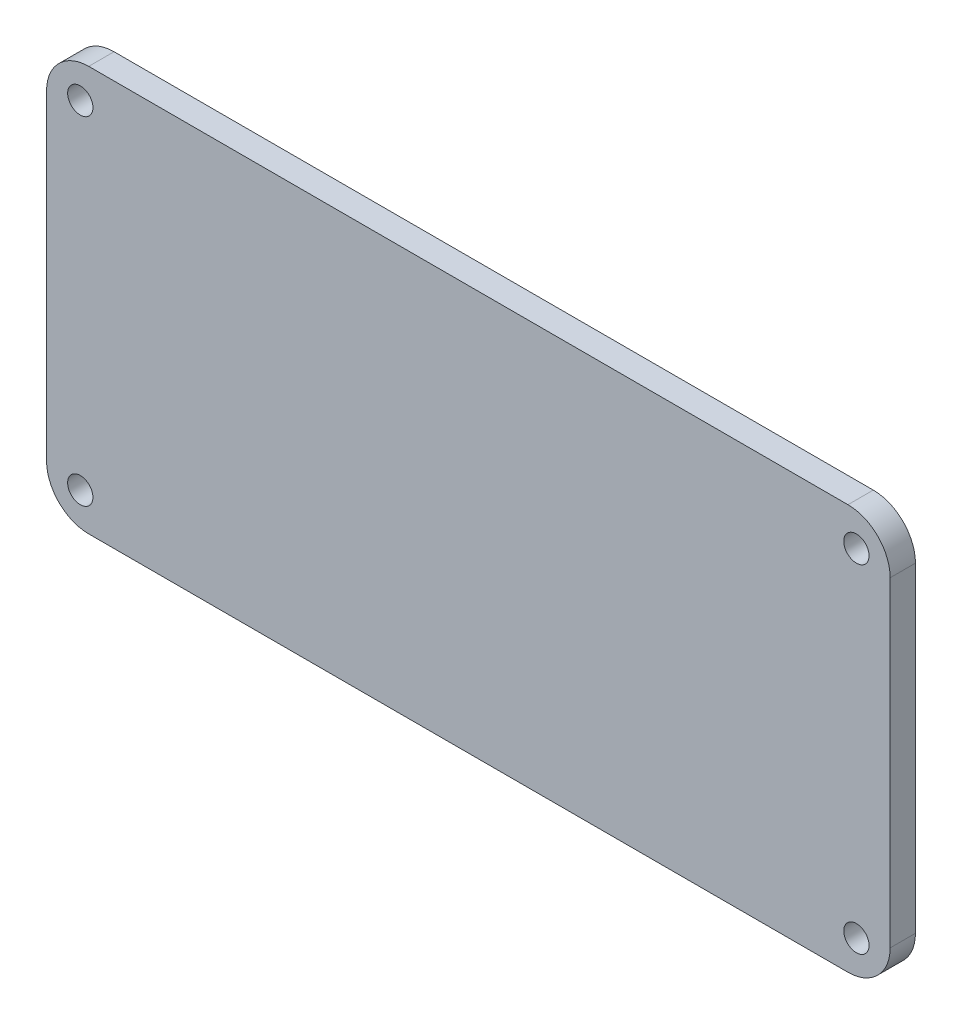
SolidWorks part; units mm, degrees
ref_plane "前视基准面" through (0, 0, 0) normal (0, 0, 1) x (1, 0, 0)
ref_plane "上视基准面" through (0, 0, 0) normal (0, 1, 0) x (1, 0, 0)
ref_plane "右视基准面" through (0, 0, 0) normal (1, 0, 0) x (0, 0, -1)
other "Configuration Table"
sketch "草图1" plane through (0, 0, 0) normal (0, 0, 1) x (1, 0, 0)
  line L1 (-45, 24) -> (45, 24)
  line L2 (-50, 19) -> (-50, -19)
  line L3 (-45, -24) -> (45, -24)
  line L4 (50, 19) -> (50, -19)
  line L5 (-50, 24) -> (50, -24) construction
  line L6 (-50, -24) -> (50, 24) construction
  arc A0 (-50, 19) -> (-45, 24) centre (-45, 19) cw
  arc A1 (50, 19) -> (45, 24) centre (45, 19) ccw
  arc A2 (45, -24) -> (50, -19) centre (45, -19) ccw
  arc A3 (-45, -24) -> (-50, -19) centre (-45, -19) cw
  point P0 (0, 0)
  dimension "D3" = 5
  dimension "D4" = 5
  dimension "D5" = 5
  dimension "D6" = 5
  dimension "D1" = 100
  dimension "D2" = 48
extrude "凸台-拉伸1" add sketch "草图1" along normal blind 3
sketch "草图2" plane through (0, 0, 3) normal (0, 0, 1) x (1, 0, 0)
  line L0 (45, 24) -> (-45, 24) construction
  line L1 (-50, 19) -> (-50, -19) construction
  circle A0 centre (-46, 20) radius 1.5
  circle A1 centre (46, 20) radius 1.5
  circle A2 centre (-46, -20) radius 1.5
  circle A3 centre (46, -20) radius 1.5
  dimension "D1" = 3
  dimension "D2" = 4
  dimension "D3" = 4
  dimension "D6" = 40
  dimension "D4" = 2
  dimension "D5" = 2
extrude "切除-拉伸1" cut sketch "草图2" against normal blind 3
